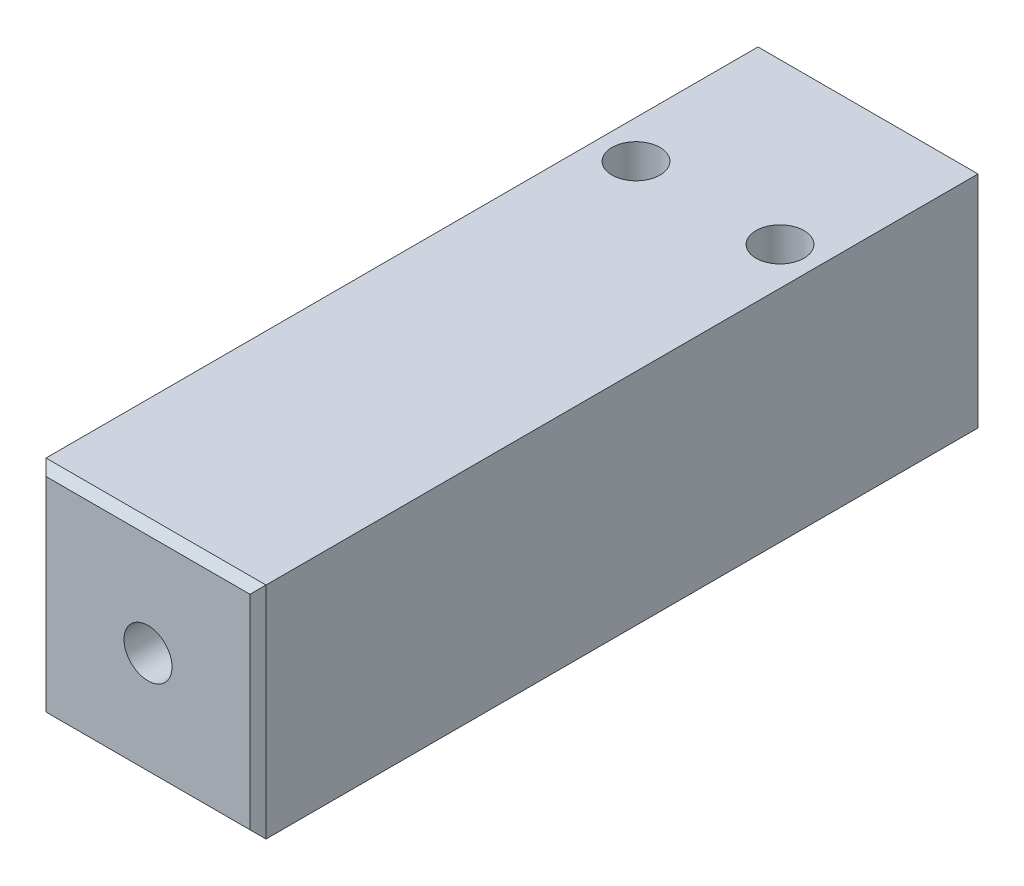
SolidWorks part; units mm, degrees
ref_plane "Alzado" through (0, 0, 0) normal (0, 0, 1) x (1, 0, 0)
ref_plane "Planta" through (0, 0, 0) normal (0, 1, 0) x (1, 0, 0)
ref_plane "Vista lateral" through (0, 0, 0) normal (1, 0, 0) x (0, 0, -1)
sketch "Croquis1" plane through (0, 0, 0) normal (0, 0, 1) x (1, 0, 0)
  line L1 (-27.5, 27.5) -> (27.5, 27.5)
  line L2 (-27.5, 27.5) -> (-27.5, -27.5)
  line L3 (-27.5, -27.5) -> (27.5, -27.5)
  line L4 (27.5, 27.5) -> (27.5, -27.5)
  line L5 (-27.5, 27.5) -> (27.5, -27.5) construction
  line L6 (-27.5, -27.5) -> (27.5, 27.5) construction
  point P0 (0, 0)
  dimension "D1" = 55
  dimension "D2" = 55
extrude "Saliente-Extruir1" add sketch "Croquis1" against normal blind 180
sketch "Croquis2" plane through (0, 0, 0) normal (0, 0, 1) x (1, 0, 0)
  circle A0 centre (0, 0) radius 6
  dimension "D1" = 12
extrude "Cortar-Extruir1" cut sketch "Croquis2" against normal blind 30
sketch "Croquis3" plane through (0, 0, -180) normal (0, 0, -1) x (-1, 0, 0)
  circle A0 centre (18, 18) radius 4
  circle A1 centre (-18, 18) radius 4
  circle A2 centre (-18, -18) radius 4
  circle A3 centre (18, -18) radius 4
  dimension "D2" = 18
  dimension "D9" = 8
  dimension "D10" = 8
  dimension "D11" = 8
  dimension "D12" = 8
  dimension "D1" = 18
  dimension "D3" = 18
  dimension "D4" = 18
  dimension "D5" = 18
  dimension "D6" = 18
  dimension "D7" = 18
  dimension "D8" = 18
extrude "Cortar-Extruir2" cut sketch "Croquis3" against normal blind 25
sketch "Croquis6" plane through (0, 27.5, 0) normal (0, 1, 0) x (1, 0, 0)
  line L0 (27.5, 180) -> (-27.5, 180) construction
  circle A0 centre (-18, 140) radius 6
  circle A1 centre (18, 140) radius 6
  dimension "D1" = 40
  dimension "D2" = 40
  dimension "D3" = 18
  dimension "D5" = 12
  dimension "D6" = 12
  dimension "D4" = 18
extrude "Cortar-Extruir5" cut sketch "Croquis6" against normal blind 12
chamfer "Chaflán1" distance 2 angle 45 4 edges at (0, -27.5, 0) (-27.5, 0, 0) (27.5, 0, 0) (0, 27.5, 0)
